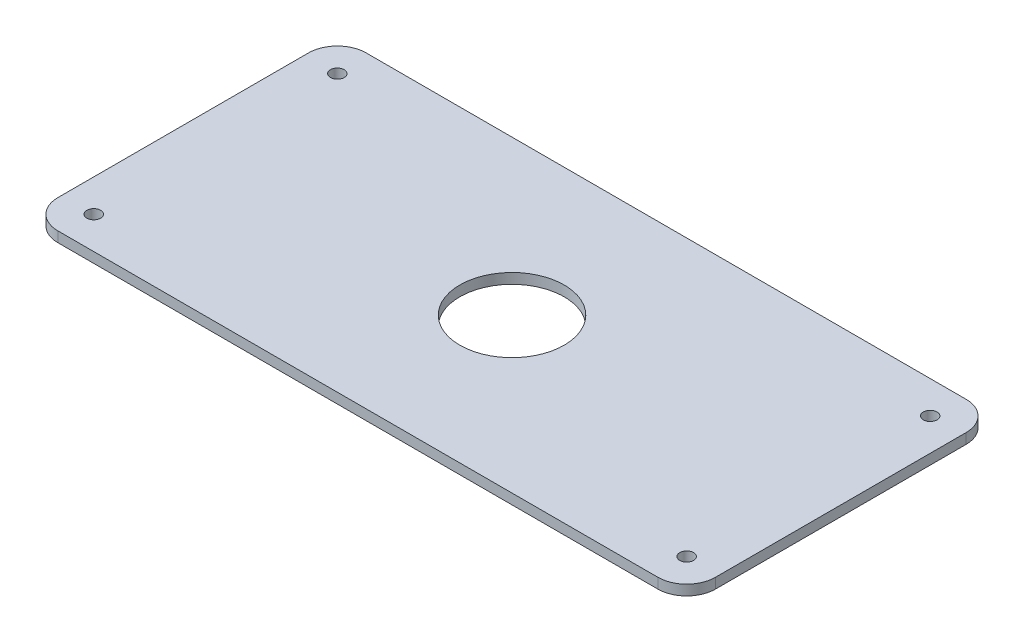
SolidWorks part; units mm, degrees
ref_plane "Front Plane" through (0, 0, 0) normal (0, 0, 1) x (1, 0, 0)
ref_plane "Top Plane" through (0, 0, 0) normal (0, 1, 0) x (1, 0, 0)
ref_plane "Right Plane" through (0, 0, 0) normal (1, 0, 0) x (0, 0, -1)
sketch "Sketch1" plane through (0, 0, 0) normal (0, 1, 0) x (1, 0, 0)
  line L1 (-203.2, -95.25) -> (203.2, -95.25)
  line L2 (-203.2, -95.25) -> (-203.2, 95.25)
  line L3 (-203.2, 95.25) -> (203.2, 95.25)
  line L4 (203.2, -95.25) -> (203.2, 95.25)
  line L5 (-203.2, -95.25) -> (203.2, 95.25) construction
  line L6 (-203.2, 95.25) -> (203.2, -95.25) construction
  point P0 (0, 0)
  dimension "D1" = 406.4
  dimension "D2" = 190.5
extrude "Boss-Extrude1" add sketch "Sketch1" along normal blind 6.35
sketch "Sketch2" plane through (0, 6.35, 0) normal (0, 1, 0) x (1, 0, 0)
  circle A0 centre (0, 0) radius 31.75 construction
  circle A1 centre (0, 0) radius 32.25
  dimension "D1" = 63.5
  dimension "D2" = 0.5
extrude "Cut-Extrude1" cut sketch "Sketch2" against normal through all
sketch "Sketch3" plane through (0, 6.35, 0) normal (0, 1, 0) x (1, 0, 0)
  line L0 (-203.2, 95.25) -> (-203.2, -95.25) construction
  line L1 (-183.2, 75.25) -> (183.2, 75.25) construction
  line L2 (-183.2, 75.25) -> (-183.2, -75.25) construction
  line L3 (-183.2, -75.25) -> (183.2, -75.25) construction
  line L4 (183.2, 75.25) -> (183.2, -75.25) construction
  line L5 (203.2, 95.25) -> (-203.2, 95.25) construction
  line L6 (-203.2, -95.25) -> (203.2, -95.25) construction
  line L7 (203.2, -95.25) -> (203.2, 95.25) construction
  circle A0 centre (-183.2, 75.25) radius 4.25
  circle A1 centre (183.2, 75.25) radius 4.25
  circle A2 centre (183.2, -75.25) radius 4.25
  circle A3 centre (-183.2, -75.25) radius 4.25
  dimension "D5" = 8.5
  dimension "D1" = 20
  dimension "D2" = 20
  dimension "D3" = 20
  dimension "D4" = 20
extrude "Cut-Extrude2" cut sketch "Sketch3" against normal through all
fillet "Fillet1" radius 17.78 4 edges at (-203.2, 3.175, 95.25) (-203.2, 3.175, -95.25) (203.2, 3.175, -95.25) (203.2, 3.175, 95.25)
